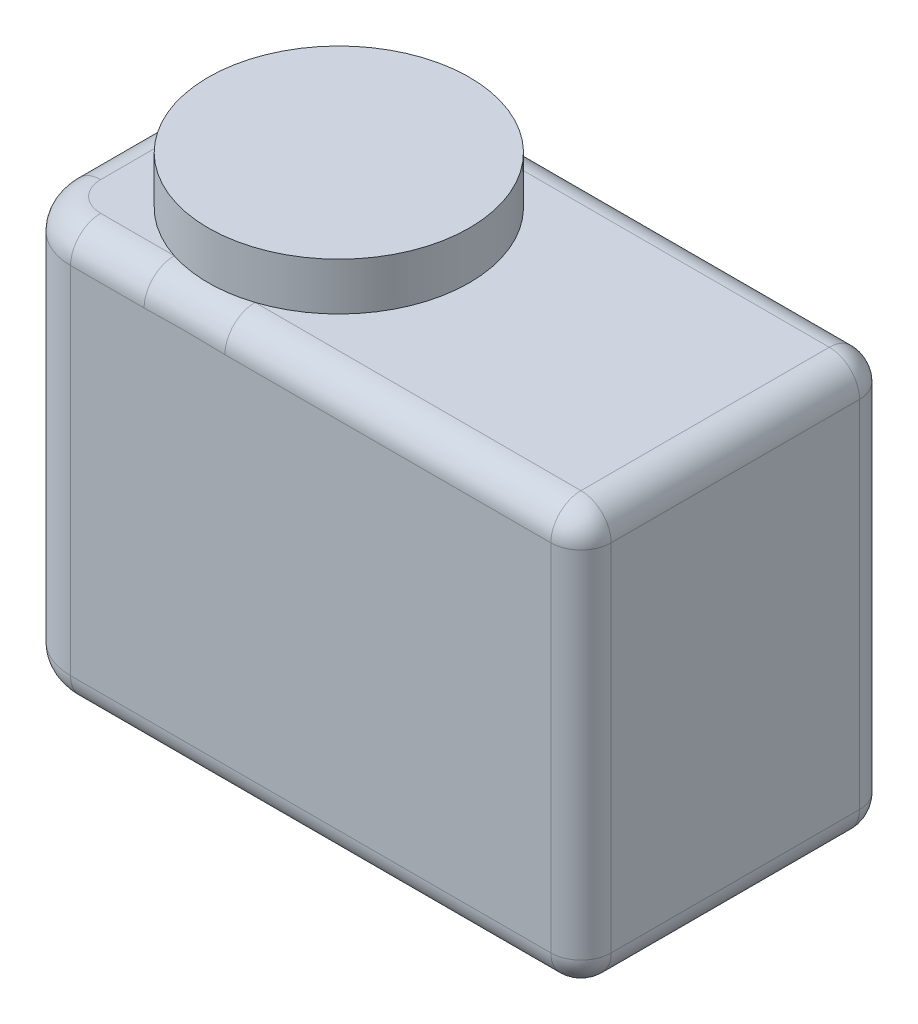
SolidWorks part; units mm, degrees
ref_plane "Front Plane" through (0, 0, 0) normal (0, 0, 1) x (1, 0, 0)
ref_plane "Top Plane" through (0, 0, 0) normal (0, 1, 0) x (1, 0, 0)
ref_plane "Right Plane" through (0, 0, 0) normal (1, 0, 0) x (0, 0, -1)
sketch "Sketch1" plane through (0, 0, 0) normal (0, 1, 0) x (1, 0, 0)
  line L1 (-19, -13) -> (24, -13)
  line L2 (-24, -8) -> (-24, 8)
  line L3 (-19, 13) -> (24, 13)
  line L4 (24, -13) -> (24, 13)
  line L5 (-24, -13) -> (24, 13) construction
  line L6 (-24, 13) -> (24, -13) construction
  arc A0 (-19, -13) -> (-24, -8) centre (-19, -8) cw
  arc A1 (-24, 8) -> (-19, 13) centre (-19, 8) cw
  point P0 (0, 0)
  dimension "D2" = 5
  dimension "D1" = 26
  dimension "26mm" = 48
extrude "Boss-Extrude1" add sketch "Sketch1" along normal blind 35 contours L3 L4 L1 A0 L2 A1
sketch "Sketch2" plane through (0, 35, 0) normal (0, 1, 0) x (1, 0, 0)
  line L0 (24, 0) -> (-9.4, 0) construction
  line L1 (24, -13) -> (24, 13) construction
  circle A0 centre (-9.4, 0) radius 11
  dimension "D2" = 22
  dimension "D1" = 33.4
extrude "Boss-Extrude2" add sketch "Sketch2" along normal blind 4
fillet "Fillet1" radius 2.54 10 edges at (2.5, 0, 13) (-22.5355, 0, 11.5355) (2.5, 0, -13) (-22.5355, 0, -11.5355) (2.5, 35, -13) (-22.5355, 35, -11.5355) (-24, 35, 0) (-22.5355, 35, 11.5355) (-24, 0, 0) (2.5, 35, 13)
fillet "Fillet2" radius 2.54 8 edges at (24, 34.2561, 12.2561) (24, 35, 0) (24, 34.2561, -12.2561) (24, 17.5, -13) (24, 0.7439, -12.2561) (24, 0, 0) (24, 0.7439, 12.2561) (24, 17.5, 13)
equation "\"mm3.60257252in\"=3.60257"
